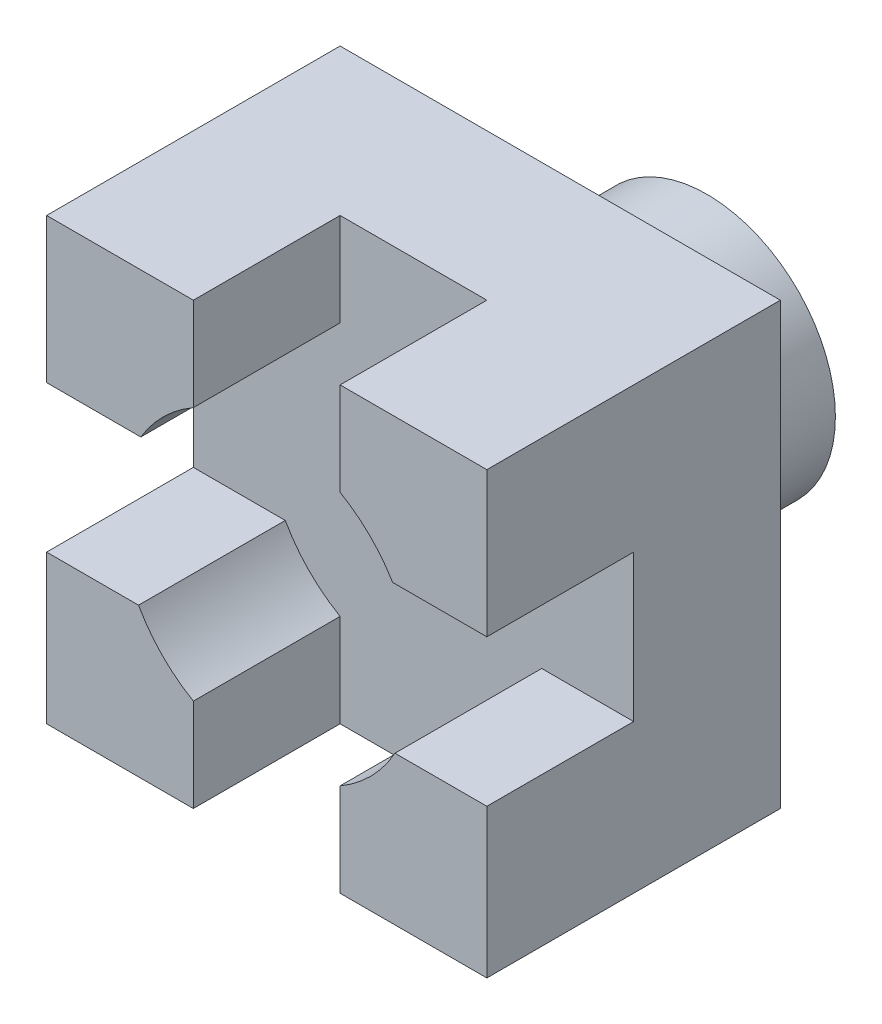
SolidWorks part; units mm, degrees
ref_plane "Front Plane" through (0, 0, 0) normal (0, 0, 1) x (1, 0, 0)
ref_plane "Top Plane" through (0, 0, 0) normal (0, 1, 0) x (1, 0, 0)
ref_plane "Right Plane" through (0, 0, 0) normal (1, 0, 0) x (0, 0, -1)
sketch "Sketch1" plane through (0, 0, 0) normal (0, 0, 1) x (1, 0, 0)
  circle A0 centre (-39.9679, 24.7914) radius 1
  circle A1 centre (-39.9679, 24.7914) radius 1.75
extrude "Boss-Extrude1" add sketch "Sketch1" along normal blind 2
sketch "Sketch4" plane through (0, 0, 2) normal (0, 0, 1) x (1, 0, 0)
  line L1 (-42.9679, 27.7914) -> (-36.9679, 27.7914)
  line L2 (-42.9679, 27.7914) -> (-42.9679, 21.7914)
  line L3 (-42.9679, 21.7914) -> (-36.9679, 21.7914)
  line L4 (-36.9679, 27.7914) -> (-36.9679, 21.7914)
  line L5 (-42.9679, 27.7914) -> (-36.9679, 21.7914) construction
  line L6 (-42.9679, 21.7914) -> (-36.9679, 27.7914) construction
  point P0 (-39.9679, 24.7914)
extrude "Boss-Extrude2" add sketch "Sketch4" along normal blind 4
sketch "Sketch5" plane through (0, 0, 6) normal (0, 0, 1) x (1, 0, 0)
  line L0 (-36.9679, 25.8182) -> (-36.9679, 23.8182)
  line L2 (-36.9679, 27.7914) -> (-42.9679, 27.7914) construction
  line L5 (-40.9679, 24.7914) -> (-40.9679, 27.7914)
  line L6 (-38.9679, 24.7914) -> (-38.9679, 27.7914)
  line L7 (-40.9679, 27.7914) -> (-38.9679, 27.7914)
  line L8 (-38.9679, 21.7914) -> (-40.9679, 21.7914)
  line L9 (-42.9679, 21.7914) -> (-36.9679, 21.7914) construction
  line L10 (-42.9679, 23.8182) -> (-42.9679, 25.8182)
  line L11 (-40.9679, 21.7914) -> (-40.9679, 24.7914)
  line L12 (-38.9679, 24.7914) -> (-38.9679, 21.7914)
  line L13 (-39.9679, 23.8182) -> (-42.9679, 23.8182)
  line L14 (-39.9679, 25.8182) -> (-36.9679, 25.8182)
  line L15 (-42.9679, 25.8182) -> (-39.9679, 25.8182)
  line L16 (-39.9679, 23.8182) -> (-36.9679, 23.8182)
  line L17 (-39.9679, 23.8182) -> (-39.9679, 23.5798)
  circle A1 centre (-39.9679, 24.7914) radius 2
extrude "Cut-Extrude4" cut sketch "Sketch5" against normal blind 2
